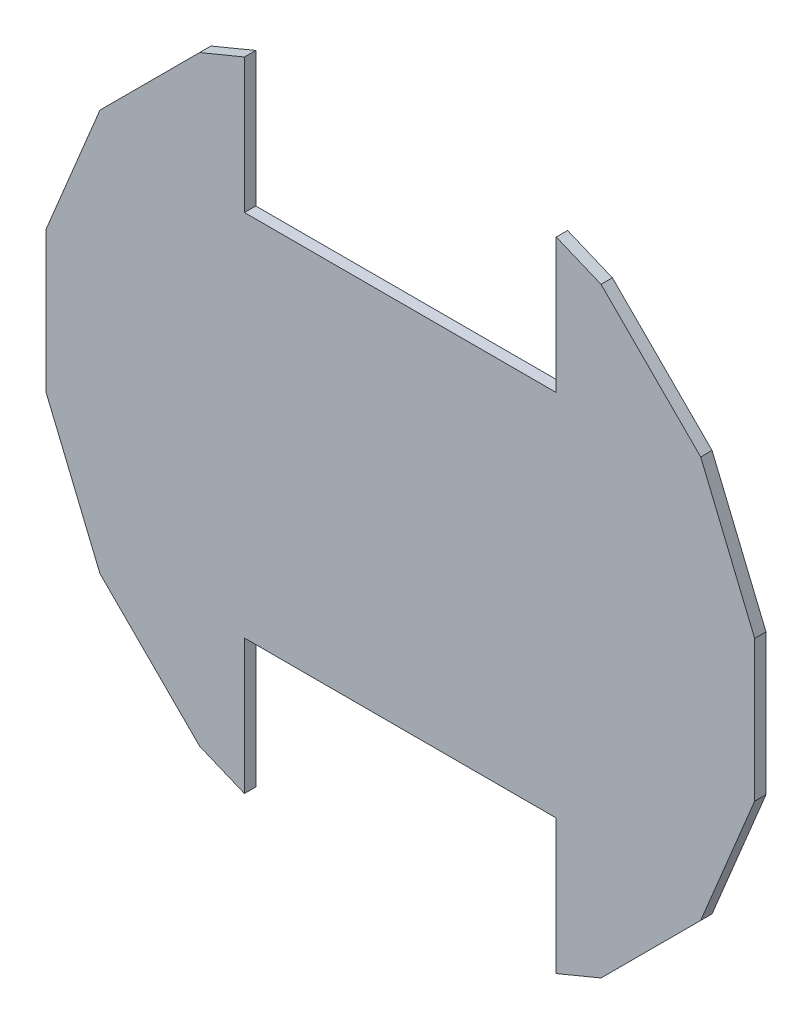
SolidWorks part; units mm, degrees
ref_plane "前视基准面" through (0, 0, 0) normal (0, 0, 1) x (1, 0, 0)
ref_plane "上视基准面" through (0, 0, 0) normal (0, 1, 0) x (1, 0, 0)
ref_plane "右视基准面" through (0, 0, 0) normal (1, 0, 0) x (0, 0, -1)
sketch "草图1" plane through (0, 0, 0) normal (0, 0, 1) x (1, 0, 0)
  line L0 (0, 0) -> (42.435, 0) construction
  line L1 (0, -42.435) -> (0, 42.435) construction
  line L2 (42.435, -42.435) -> (42.435, 42.435) construction
  line L3 (42.435, 42.435) -> (0, 42.435) construction
  line L4 (0, 42.435) -> (-42.435, 42.435) construction
  line L5 (-42.435, 42.435) -> (-42.435, -42.435) construction
  line L6 (0, -42.435) -> (-42.435, -42.435) construction
  line L7 (42.435, -42.435) -> (0, -42.435) construction
  line L8 (-22, -26) -> (22, -26)
  line L21 (50, 9.9456) -> (42.388, 28.3227)
  line L22 (42.388, 28.3227) -> (28.3227, 42.388)
  line L23 (28.3227, 42.388) -> (9.9456, 50)
  line L24 (9.9456, 50) -> (-9.9456, 50)
  line L25 (-9.9456, 50) -> (-28.3227, 42.388)
  line L26 (-28.3227, 42.388) -> (-42.388, 28.3227)
  line L27 (-42.388, 28.3227) -> (-50, 9.9456)
  line L28 (-50, 9.9456) -> (-50, -9.9456)
  line L29 (-50, -9.9456) -> (-42.388, -28.3227)
  line L30 (-42.388, -28.3227) -> (-28.3227, -42.388)
  line L31 (-28.3227, -42.388) -> (-9.9456, -50)
  line L32 (-9.9456, -50) -> (9.9456, -50)
  line L33 (9.9456, -50) -> (28.3227, -42.388)
  line L34 (28.3227, -42.388) -> (42.388, -28.3227)
  line L35 (42.388, -28.3227) -> (50, -9.9456)
  line L36 (50, -9.9456) -> (50, 9.9456)
  line L41 (22, -26) -> (22, -63.2104)
  line L42 (22, -63.2104) -> (-22, -63.2104)
  line L43 (-22, -26) -> (-22, -63.2104)
  line L44 (-22, 26) -> (22, 26)
  line L45 (22, 26) -> (22, 63.2104)
  line L46 (22, 63.2104) -> (-22, 63.2104)
  line L47 (-22, 26) -> (-22, 63.2104)
  circle A0 centre (0, 0) radius 50 construction
  point P10 (-42.435, 0)
  point P32 (0, -49.6322)
  point P34 (0, -63.2104)
  point P35 (0, -26)
  dimension "D1" = 24
  dimension "D2" = 22
extrude "凸台-拉伸1" add sketch "草图1" along normal blind 1.6 contours L44 L47 L25 L26 L27 L28 L29 L30 L31 L43 L8 L41 L33 L34 L35 L36 L21 L22 L23 L45
